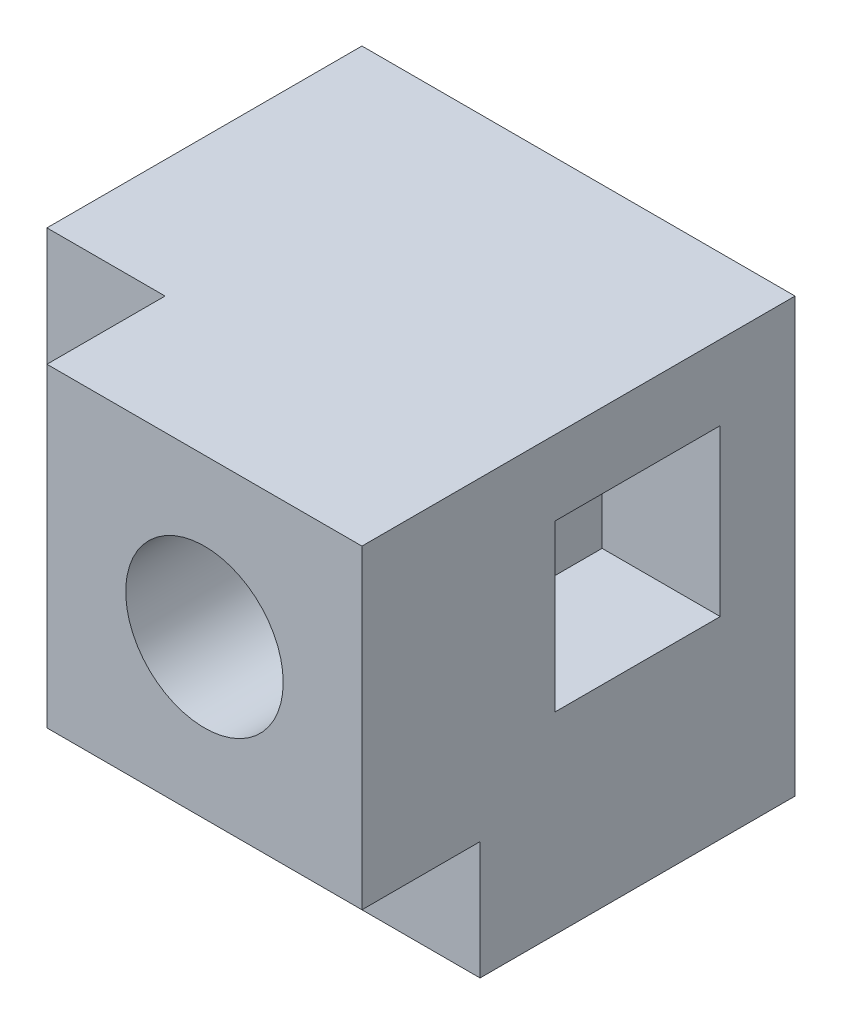
SolidWorks part; units mm, degrees
ref_plane "Plan de face" through (0, 0, 0) normal (0, 0, 1) x (1, 0, 0)
ref_plane "Plan de dessus" through (0, 0, 0) normal (0, 1, 0) x (1, 0, 0)
ref_plane "Plan de droite" through (0, 0, 0) normal (1, 0, 0) x (0, 0, -1)
sketch "Esquisse2" plane through (0, 0, 0) normal (0, 1, 0) x (1, 0, 0)
  line L1 (-40, 40) -> (40, 40)
  line L2 (-40, 40) -> (-40, -40)
  line L3 (-40, -40) -> (40, -40)
  line L4 (40, 40) -> (40, -40)
  line L5 (-40, 40) -> (40, -40) construction
  line L6 (-40, -40) -> (40, 40) construction
  point P0 (0, 0)
  dimension "D1" = 80
  dimension "D2" = 80
extrude "Boss.-Extru.1" add sketch "Esquisse2" along normal blind 80
sketch "Esquisse5" plane through (-40, 0, 0) normal (-1, 0, 0) x (0, 0, 1)
  line L1 (-40, 80) -> (40, 80)
  line L2 (-40, 80) -> (-40, 0)
  line L3 (-40, 0) -> (40, 0)
  line L4 (40, 80) -> (40, 0)
extrude "Boss.-Extru.2" add sketch "Esquisse5" along normal blind 30
sketch "Esquisse6" plane through (0, 0, 40) normal (0, 0, 1) x (1, 0, 0)
  line L0 (40, 40) -> (-40, 40) construction
  line L1 (40, 80) -> (40, 0) construction
  line L2 (-70, 0) -> (40, 0) construction
  line L3 (40, 80) -> (-40, 80)
  line L4 (40, 80) -> (40, 0)
  line L5 (40, 0) -> (-40, 0)
  line L6 (-40, 80) -> (-40, 0)
  dimension "D1" = 80
extrude "Boss.-Extru.3" add sketch "Esquisse6" along normal blind 30
sketch "Esquisse7" plane through (0, 0, 0) normal (0, -1, 0) x (1, 0, 0)
  line L1 (-40, 40) -> (40, 40)
  line L2 (-40, 40) -> (-40, -40)
  line L3 (-40, -40) -> (40, -40)
  line L4 (40, 40) -> (40, -40)
extrude "Boss.-Extru.4" add sketch "Esquisse7" along normal blind 30
sketch "Esquisse8" plane through (-70, 0, 0) normal (-1, 0, 0) x (0, 0, 1)
  line L0 (0, 0) -> (0, 80) construction
  line L1 (-40, 0) -> (40, 0) construction
  line L2 (40, 80) -> (-40, 80) construction
  circle A0 centre (0, 40) radius 20
  dimension "D1" = 40
extrude "Enlèv. mat.-Extru.1" cut sketch "Esquisse8" against normal blind 45
sketch "Esquisse9" plane through (0, 0, 70) normal (0, 0, 1) x (1, 0, 0)
  line L0 (0, 0) -> (0, 80) construction
  line L1 (-40, 0) -> (40, 0) construction
  line L2 (40, 80) -> (-40, 80) construction
  circle A0 centre (0, 40) radius 20
  dimension "D1" = 40
extrude "Enlèv. mat.-Extru.2" cut sketch "Esquisse9" against normal blind 45
sketch "Esquisse10" plane through (0, -30, 0) normal (0, -1, 0) x (1, 0, 0)
  line L0 (40, 0) -> (-40, 0) construction
  line L1 (40, -40) -> (40, 40) construction
  line L2 (-40, 40) -> (-40, -40) construction
  circle A0 centre (0, 0) radius 20
  dimension "D1" = 40
extrude "Enlèv. mat.-Extru.3" cut sketch "Esquisse10" against normal blind 45
sketch "Esquisse11" plane through (40, 0, 0) normal (1, 0, 0) x (0, 0, -1)
  line L0 (-40, 0) -> (-40, 80) construction
  line L1 (-70, 80) -> (40, 80) construction
  line L2 (-40, 80) -> (40, 0) construction
  line L3 (40, 0) -> (-40, 0) construction
  line L4 (-40, 0) -> (40, 80) construction
  line L5 (40, 80) -> (40, -30) construction
  line L7 (21, 19) -> (-21, 19)
  line L8 (21, 19) -> (21, 61)
  line L9 (21, 61) -> (-21, 61)
  line L10 (-21, 19) -> (-21, 61)
  line L11 (21, 19) -> (-21, 61) construction
  line L12 (21, 61) -> (-21, 19) construction
  point P5 (0, 40)
  dimension "D1" = 42
extrude "Enlèv. mat.-Extru.4" cut sketch "Esquisse11" against normal blind 30
equation "\"40u\"=50.2739"
